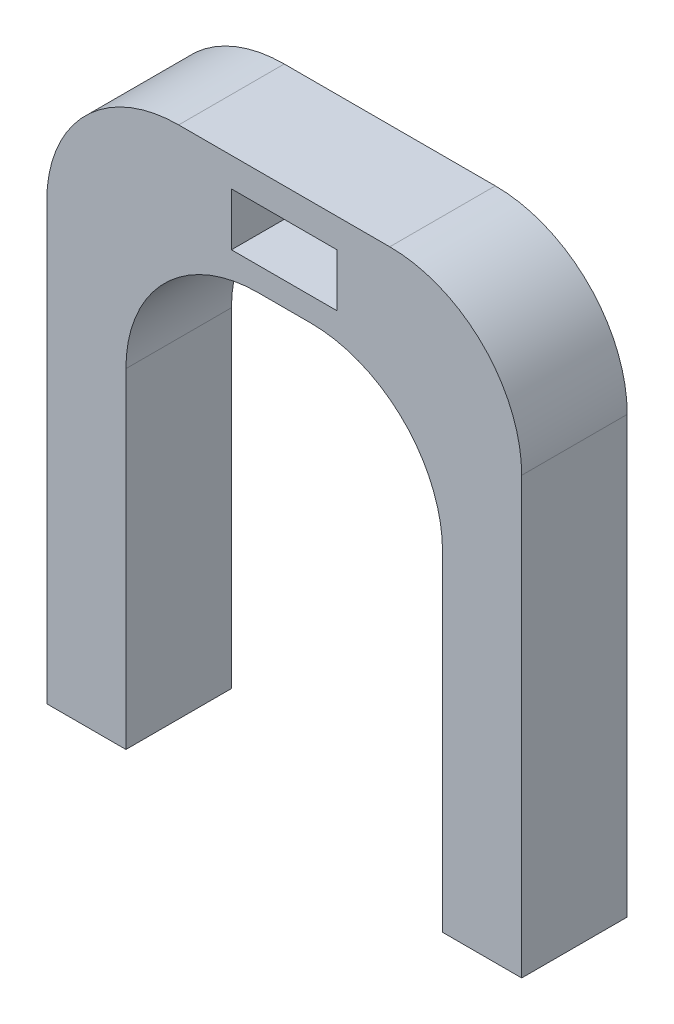
SolidWorks part; units mm, degrees
ref_plane "正面" through (0, 0, 0) normal (0, 0, 1) x (1, 0, 0)
ref_plane "平面" through (0, 0, 0) normal (0, 1, 0) x (1, 0, 0)
ref_plane "右側面" through (0, 0, 0) normal (1, 0, 0) x (0, 0, -1)
sketch "ｽｹｯﾁ2" plane through (0, 0, 0) normal (0, 0, 1) x (1, 0, 0)
  line L1 (0, 0) -> (18, 0)
  line L2 (0, 0) -> (0, 21.5)
  line L3 (0, 21.5) -> (18, 21.5)
  line L4 (18, 0) -> (18, 21.5)
  dimension "D1" = 21.5
  dimension "D2" = 18
extrude "ﾎﾞｽ - 押し出し1" add sketch "ｽｹｯﾁ2" along normal blind 4
sketch "ｽｹｯﾁ3" plane through (0, 0, 4) normal (0, 0, 1) x (1, 0, 0)
  line L0 (0, 0) -> (18, 0) construction
  line L1 (3, 0) -> (15, 0)
  line L2 (3, 0) -> (3, 17.5)
  line L3 (3, 17.5) -> (15, 17.5)
  line L4 (15, 0) -> (15, 17.5)
  line L5 (0, 21.5) -> (0, 0) construction
  line L6 (18, 0) -> (18, 21.5) construction
  line L7 (18, 21.5) -> (0, 21.5) construction
  dimension "D1" = 3
  dimension "D2" = 3
  dimension "D3" = 4
extrude "ｶｯﾄ - 押し出し1" cut sketch "ｽｹｯﾁ3" against normal through all
fillet "ﾌｨﾚｯﾄ1" radius 5 2 edges at (15, 17.5, 2) (3, 17.5, 2)
fillet "ﾌｨﾚｯﾄ2" radius 5 2 edges at (18, 21.5, 2) (0, 21.5, 2)
sketch "ｽｹｯﾁ4" plane through (0, 0, 4) normal (0, 0, 1) x (1, 0, 0)
  line L0 (0, 16.5) -> (0, 0) construction
  line L1 (7, 20.4009) -> (11, 20.4009)
  line L2 (7, 20.4009) -> (7, 18.4009)
  line L3 (7, 18.4009) -> (11, 18.4009)
  line L4 (11, 20.4009) -> (11, 18.4009)
  dimension "D1" = 2
  dimension "D2" = 4
  dimension "D3" = 7
extrude "ｶｯﾄ - 押し出し2" cut sketch "ｽｹｯﾁ4" against normal through all
